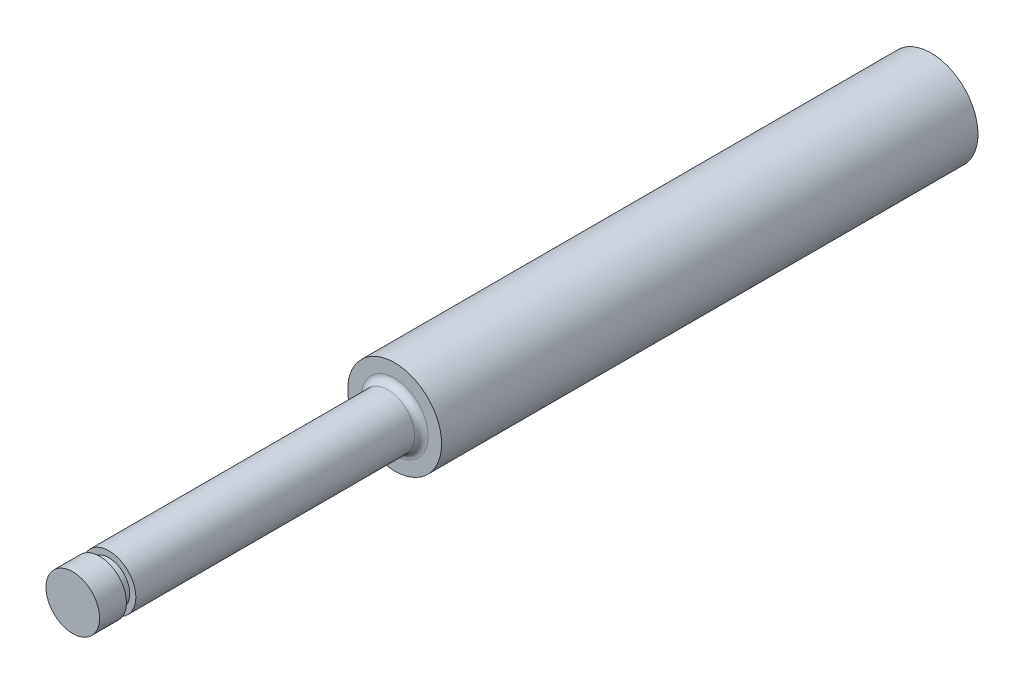
SolidWorks part; units mm, degrees
ref_plane "Plan1" through (0, 0, 0) normal (0, 0, 1) x (1, 0, 0)
ref_plane "Plan2" through (0, 0, 0) normal (0, 1, 0) x (1, 0, 0)
ref_plane "Plan3" through (0, 0, 0) normal (1, 0, 0) x (0, 0, -1)
sketch "Esquisse1" plane through (0, 0, 0) normal (0, 0, 1) x (1, 0, 0)
  circle A0 centre (0, 0) radius 3.5
  dimension "D1" = 7
extrude "Base-Extrusion" add sketch "Esquisse1" along normal blind 40
sketch "Esquisse2" plane through (0, 0, 0) normal (0, 0, -1) x (-1, 0, 0)
  circle A0 centre (0, 0) radius 2
  dimension "D1" = 4
extrude "Boss.-Extru.1" add sketch "Esquisse2" against normal blind 61.3
sketch "Esquisse3" plane through (0, 0, 61.3) normal (0, 0, 1) x (1, 0, 0)
  circle A0 centre (0, 0) radius 1.55
  dimension "D1" = 3.1
extrude "Boss.-Extru.2" add sketch "Esquisse3" along normal blind 0.7
sketch "Esquisse4" plane through (0, 0, 62) normal (0, 0, 1) x (1, 0, 0)
  circle A0 centre (0, 0) radius 2
  dimension "D1" = 4
extrude "Boss.-Extru.3" add sketch "Esquisse4" along normal blind 2
fillet "Congé1" radius 0.5
hole_wizard "Perçage1" positions "Esquisse6" profile "Esquisse5" legacy
sketch "Esquisse6" plane through (0, 0, 0) normal (0, 0, -1) x (-1, 0, 0)
  point P0 (0, 0)
sketch "Esquisse5" plane through (0, 0, 0) normal (1, 0, 0) x (0, 1, 0)
  line L0 (0, 0) -> (0, 11.433)
  line L1 (0, 11.433) -> (0.75, 11)
  line L2 (0.75, 11) -> (0.75, 8)
  line L3 (0.75, 8) -> (1.5, 8)
  line L4 (1.5, 0) -> (0, 0)
  line L5 (0, -11.3109) -> (0, 121.1557) construction
  line L6 (0, 11.433) -> (-0.75, 11) construction
  line L7 (1.5, 8) -> (1.5, 0)
  dimension "Diamètre" = 1.5
  dimension "Profondeur" = 11
  dimension "Diamètre chambrage" = 3
  dimension "Profondeur chambrage" = 8
  dimension "Angle" = 120
